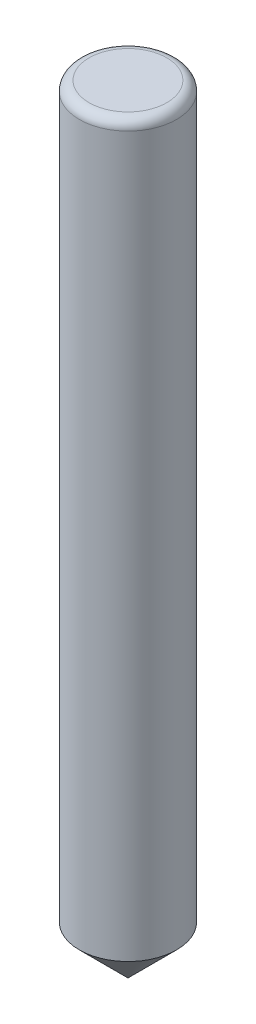
SolidWorks part; units mm, degrees
ref_plane "Front Plane" through (0, 0, 0) normal (0, 0, 1) x (1, 0, 0)
ref_plane "Top Plane" through (0, 0, 0) normal (0, 1, 0) x (1, 0, 0)
ref_plane "Right Plane" through (0, 0, 0) normal (1, 0, 0) x (0, 0, -1)
sketch "Sketch1" plane through (0, 0, 0) normal (0, 1, 0) x (1, 0, 0)
  circle A0 centre (0, 0) radius 5
  dimension "D1" = 10
extrude "Boss-Extrude1" add sketch "Sketch1" along normal blind 80
chamfer "Chamfer1" distance 5 angle 45 1 edges at (0, 0, 5)
fillet "Fillet1" radius 1 1 edges at (0, 80, 5)
